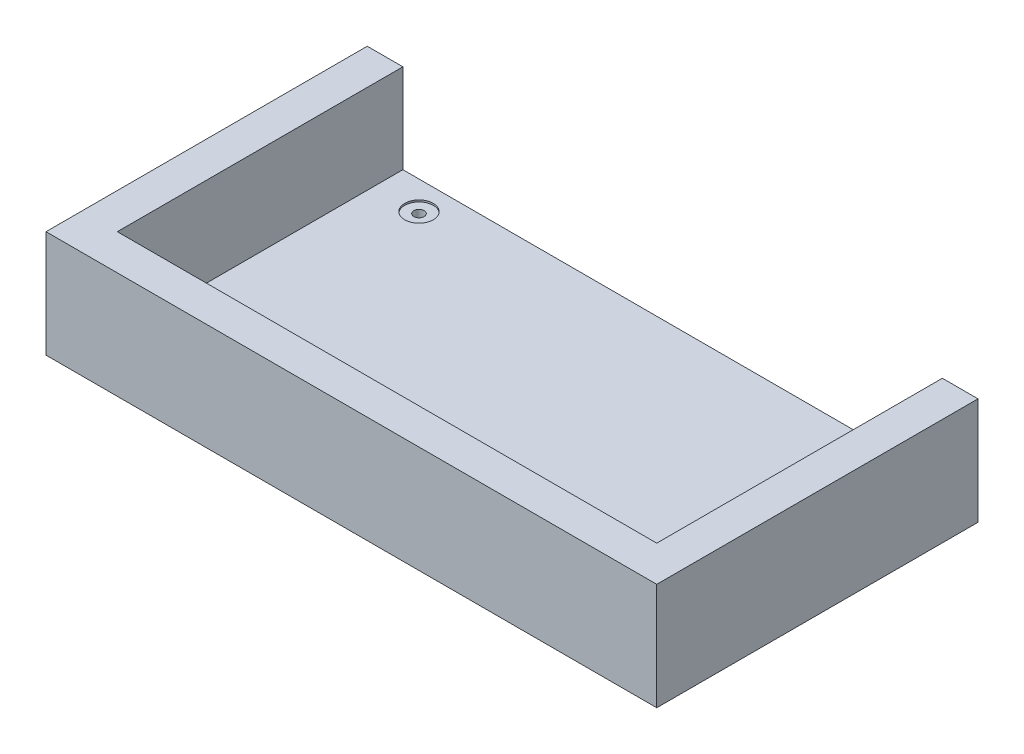
SolidWorks part; units mm, degrees
material "ABS"
ref_plane "Front Plane" through (0, 0, 0) normal (0, 0, 1) x (1, 0, 0)
ref_plane "Top Plane" through (0, 0, 0) normal (0, 1, 0) x (1, 0, 0)
ref_plane "Right Plane" through (0, 0, 0) normal (1, 0, 0) x (0, 0, -1)
sketch "Sketch1" plane through (0, 0, 0) normal (0, 1, 0) x (1, 0, 0)
  line L1 (-53.6717, 53.3702) -> (97.6583, 53.3702)
  line L2 (-53.6717, 53.3702) -> (-53.6717, -26.7498)
  line L3 (-53.6717, -26.7498) -> (97.6583, -26.7498)
  line L4 (97.6583, 53.3702) -> (97.6583, -26.7498)
  dimension "D1" = 151.33
  dimension "D2" = 80.12
extrude "Boss-Extrude1" add sketch "Sketch1" along normal blind 5
sketch "Sketch3" plane through (0, 0, 0) normal (0, 1, 0) x (1, 0, 0)
  line L1 (-53.6717, 53.3702) -> (-63.6717, 53.3702)
  line L2 (-53.6717, 53.3702) -> (-53.6717, -36.7498)
  line L3 (-53.6717, -36.7498) -> (-63.6717, -36.7498)
  line L4 (-63.6717, 53.3702) -> (-63.6717, -36.7498)
  line L5 (97.6583, 53.3702) -> (107.6583, 53.3702)
  line L6 (97.6583, 53.3702) -> (97.6583, -36.7498)
  line L7 (97.6583, -36.7498) -> (107.6583, -36.7498)
  line L8 (107.6583, 53.3702) -> (107.6583, -36.7498)
  line L9 (-53.6717, -36.7498) -> (97.6583, -36.7498)
  line L10 (-53.6717, -36.7498) -> (-53.6717, -26.7498)
  line L11 (-53.6717, -26.7498) -> (97.6583, -26.7498)
  line L12 (97.6583, -36.7498) -> (97.6583, -26.7498)
  dimension "D1" = 90.12
  dimension "D2" = 10
  dimension "D3" = 10
extrude "Boss-Extrude2" add sketch "Sketch3" along normal blind 30 contours L1 L4 L3 L2 | L11 L2 L9 L6 | L8 L5 L6 L7
hole_wizard "CBORE for M2.5 Hexagon head bolts-Full thread-grades AB1" positions "3DSketch1" profile "Sketch7" counterbore size "M2.5" standard "GB"
sketch3d "3DSketch1"
  line L0 (-41.247, 0, 16.3368) -> (-41.247, 5, 16.3368) construction
  line L1 (-41.247, 0, -45.4632) -> (-41.247, 5, -45.4632) construction
  line L2 (86.07, 0, -45.4632) -> (86.07, 5, -45.4632) construction
  point P0 (85.7004, 5, 16.2566)
  point P2 (-41.247, 5, 16.3368)
  point P6 (-41.247, 5, -45.4632)
  point P10 (86.07, 5, -45.4632)
sketch "Sketch7" plane through (85.7004, 5, 16.2566) normal (1, 0, 0) x (0, 0, 1)
  line L0 (0, 0) -> (0, 20.8712)
  line L1 (0, 20.8712) -> (1.45, 20)
  line L2 (1.45, 20) -> (1.45, 0.5)
  line L3 (1.45, 0.5) -> (4, 0.5)
  line L4 (4, 0.5) -> (4, 0)
  line L5 (4, 0) -> (0, 0)
  line L10 (0, 20.8712) -> (-1.45, 20) construction
  line L11 (0, -6.35) -> (0, 107.95) construction
  dimension "Hole Dia." = 2.9
  dimension "Hole Depth" = 20
  dimension "C'Bore Dia." = 8
  dimension "C'Bore Depth" = 0.5
  dimension "Drill Angle" = 118
